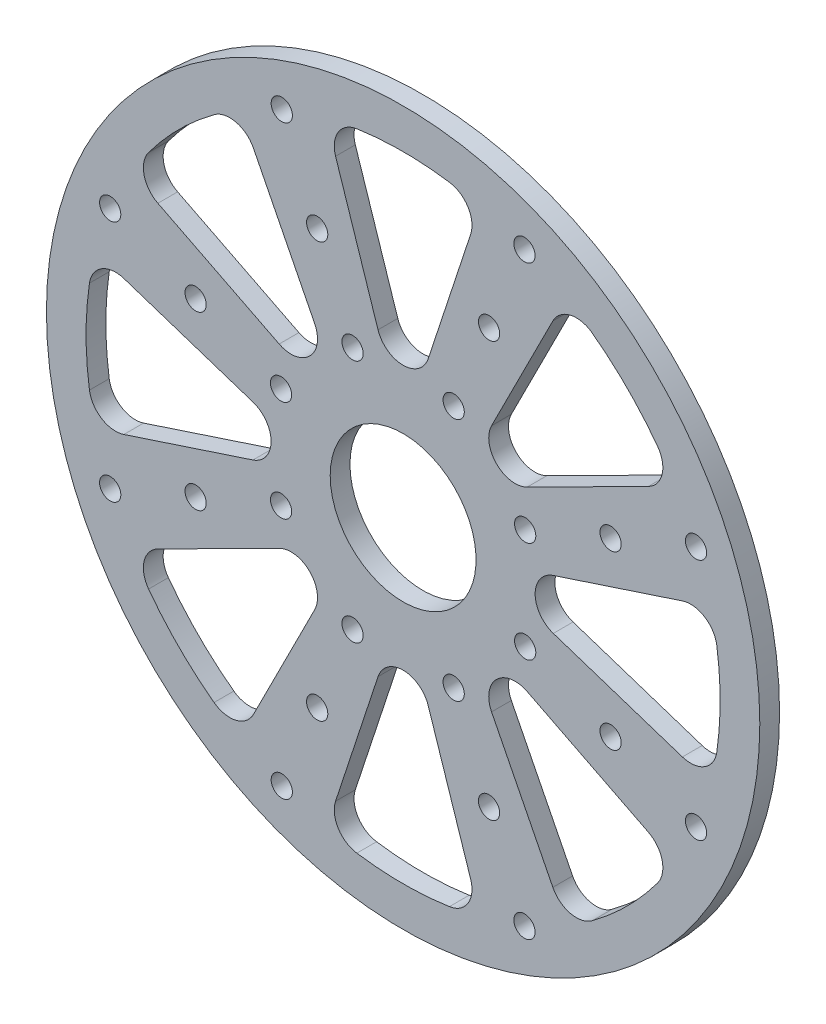
SolidWorks part; units mm, degrees
material "Plain Carbon Steel"
ref_plane "Front Plane" through (0, 0, 0) normal (0, 0, 1) x (1, 0, 0)
ref_plane "Top Plane" through (0, 0, 0) normal (0, 1, 0) x (1, 0, 0)
ref_plane "Right Plane" through (0, 0, 0) normal (1, 0, 0) x (0, 0, -1)
sketch "Sketch1" plane through (0, 0, 0) normal (0, 0, 1) x (1, 0, 0)
  circle A0 centre (0, 0) radius 85.725
  dimension "D1" = 171.45
extrude "Boss-Extrude1" add sketch "Sketch1" along normal blind 4.7498
sketch "Sketch2" plane through (0, 0, 0) normal (0, 0, -1) x (-1, 0, 0)
  line L18 (0, 24.2161) -> (0, -93.5033) construction
  line L19 (0, 0) -> (29.1605, -70.3996) construction
  line L20 (-16.2353, -67.1168) -> (-6.0321, -36.0949) construction
  line L21 (16.2353, -67.1168) -> (6.0321, -36.0949) construction
  line L22 (-16.2353, -67.1168) -> (-6.0321, -36.0949)
  line L23 (16.2353, -67.1168) -> (6.0321, -36.0949)
  line L24 (-58.9388, -35.9787) -> (-29.7883, -21.2576)
  line L25 (-35.9787, -58.9388) -> (-21.2576, -29.7883)
  line L26 (-67.1168, 16.2353) -> (-36.0949, 6.0321)
  line L27 (-67.1168, -16.2353) -> (-36.0949, -6.0321)
  line L28 (-35.9787, 58.9388) -> (-21.2576, 29.7883)
  line L29 (-58.9388, 35.9787) -> (-29.7883, 21.2576)
  line L30 (16.2353, 67.1168) -> (6.0321, 36.0949)
  line L31 (-16.2353, 67.1168) -> (-6.0321, 36.0949)
  line L32 (58.9388, 35.9787) -> (29.7883, 21.2576)
  line L33 (35.9787, 58.9388) -> (21.2576, 29.7883)
  line L34 (67.1168, -16.2353) -> (36.0949, -6.0321)
  line L35 (67.1168, 16.2353) -> (36.0949, 6.0321)
  line L36 (35.9787, -58.9388) -> (21.2576, -29.7883)
  line L37 (58.9388, -35.9787) -> (29.7883, -21.2576)
  circle A54 centre (0, 0) radius 17.526
  circle A55 centre (29.1605, -70.3996) radius 2.5527
  circle A56 centre (-29.1605, -70.3996) radius 2.5527
  circle A57 centre (-70.3996, -29.1605) radius 2.5527
  circle A58 centre (-70.3996, 29.1605) radius 2.5527
  circle A59 centre (-29.1605, 70.3996) radius 2.5527
  circle A60 centre (29.1605, 70.3996) radius 2.5527
  circle A61 centre (70.3996, 29.1605) radius 2.5527
  circle A62 centre (70.3996, -29.1605) radius 2.5527
  arc A63 (6.0321, -36.0949) -> (-6.0321, -36.0949) centre (0, -38.0788) ccw construction
  arc A64 (-16.2353, -67.1168) -> (-11.1307, -75.3827) centre (-10.2032, -69.1008) ccw construction
  arc A65 (11.1307, -75.3827) -> (16.2353, -67.1168) centre (10.2032, -69.1008) ccw construction
  arc A66 (-11.1307, -75.3827) -> (11.1307, -75.3827) centre (0, 0) ccw construction
  arc A67 (6.0321, -36.0949) -> (-6.0321, -36.0949) centre (0, -38.0788) ccw
  arc A68 (-16.2353, -67.1168) -> (-11.1307, -75.3827) centre (-10.2032, -69.1008) ccw
  circle A69 centre (20.6553, -49.8664) radius 2.5527
  circle A70 centre (12.1502, -29.3332) radius 2.5527
  circle A71 centre (-20.6553, -49.8664) radius 2.5527
  circle A72 centre (-12.1502, -29.3332) radius 2.5527
  circle A73 centre (-49.8664, -20.6553) radius 2.5527
  circle A74 centre (-29.3332, -12.1502) radius 2.5527
  circle A75 centre (-49.8664, 20.6553) radius 2.5527
  circle A76 centre (-29.3332, 12.1502) radius 2.5527
  circle A77 centre (-20.6553, 49.8664) radius 2.5527
  circle A78 centre (-12.1502, 29.3332) radius 2.5527
  circle A79 centre (20.6553, 49.8664) radius 2.5527
  circle A80 centre (12.1502, 29.3332) radius 2.5527
  circle A81 centre (49.8664, 20.6553) radius 2.5527
  circle A82 centre (29.3332, 12.1502) radius 2.5527
  circle A83 centre (49.8664, -20.6553) radius 2.5527
  circle A84 centre (29.3332, -12.1502) radius 2.5527
  arc A85 (11.1307, -75.3827) -> (16.2353, -67.1168) centre (10.2032, -69.1008) ccw
  arc A86 (-11.1307, -75.3827) -> (11.1307, -75.3827) centre (0, 0) ccw
  arc A87 (-21.2576, -29.7883) -> (-29.7883, -21.2576) centre (-26.9258, -26.9258) ccw
  arc A88 (-58.9388, -35.9787) -> (-61.1742, -45.433) centre (-56.0764, -41.6469) ccw
  arc A89 (-61.1742, -45.433) -> (-45.433, -61.1742) centre (0, 0) ccw
  arc A90 (-45.433, -61.1742) -> (-35.9787, -58.9388) centre (-41.6469, -56.0764) ccw
  arc A91 (-36.0949, -6.0321) -> (-36.0949, 6.0321) centre (-38.0788, 0) ccw
  arc A92 (-67.1168, 16.2353) -> (-75.3827, 11.1307) centre (-69.1008, 10.2032) ccw
  arc A93 (-75.3827, 11.1307) -> (-75.3827, -11.1307) centre (0, 0) ccw
  arc A94 (-75.3827, -11.1307) -> (-67.1168, -16.2353) centre (-69.1008, -10.2032) ccw
  arc A95 (-29.7883, 21.2576) -> (-21.2576, 29.7883) centre (-26.9258, 26.9258) ccw
  arc A96 (-35.9787, 58.9388) -> (-45.433, 61.1742) centre (-41.6469, 56.0764) ccw
  arc A97 (-45.433, 61.1742) -> (-61.1742, 45.433) centre (0, 0) ccw
  arc A98 (-61.1742, 45.433) -> (-58.9388, 35.9787) centre (-56.0764, 41.6469) ccw
  arc A99 (-6.0321, 36.0949) -> (6.0321, 36.0949) centre (0, 38.0788) ccw
  arc A100 (16.2353, 67.1168) -> (11.1307, 75.3827) centre (10.2032, 69.1008) ccw
  arc A101 (11.1307, 75.3827) -> (-11.1307, 75.3827) centre (0, 0) ccw
  arc A102 (-11.1307, 75.3827) -> (-16.2353, 67.1168) centre (-10.2032, 69.1008) ccw
  arc A103 (21.2576, 29.7883) -> (29.7883, 21.2576) centre (26.9258, 26.9258) ccw
  arc A104 (58.9388, 35.9787) -> (61.1742, 45.433) centre (56.0764, 41.6469) ccw
  arc A105 (61.1742, 45.433) -> (45.433, 61.1742) centre (0, 0) ccw
  arc A106 (45.433, 61.1742) -> (35.9787, 58.9388) centre (41.6469, 56.0764) ccw
  arc A107 (36.0949, 6.0321) -> (36.0949, -6.0321) centre (38.0788, 0) ccw
  arc A108 (67.1168, -16.2353) -> (75.3827, -11.1307) centre (69.1008, -10.2032) ccw
  arc A109 (75.3827, -11.1307) -> (75.3827, 11.1307) centre (0, 0) ccw
  arc A110 (75.3827, 11.1307) -> (67.1168, 16.2353) centre (69.1008, 10.2032) ccw
  arc A111 (29.7883, -21.2576) -> (21.2576, -29.7883) centre (26.9258, -26.9258) ccw
  arc A112 (35.9787, -58.9388) -> (45.433, -61.1742) centre (41.6469, -56.0764) ccw
  arc A113 (45.433, -61.1742) -> (61.1742, -45.433) centre (0, 0) ccw
  arc A114 (61.1742, -45.433) -> (58.9388, -35.9787) centre (56.0764, -41.6469) ccw
  point P78 (0, 0)
  point P100 (0, 0)
  point P120 (0, 0)
  point P153 (0, 0)
  dimension "D4" = 5.1054
  dimension "D7" = 35.052
  dimension "D3" = 76.2
  dimension "D5" = 22.5
  dimension "D9" = 22.225
  dimension "D6" = 8
  dimension "D10" = 8
  dimension "D2" = 8
extrude "Cut-Extrude1" cut sketch "Sketch2" against normal through all
